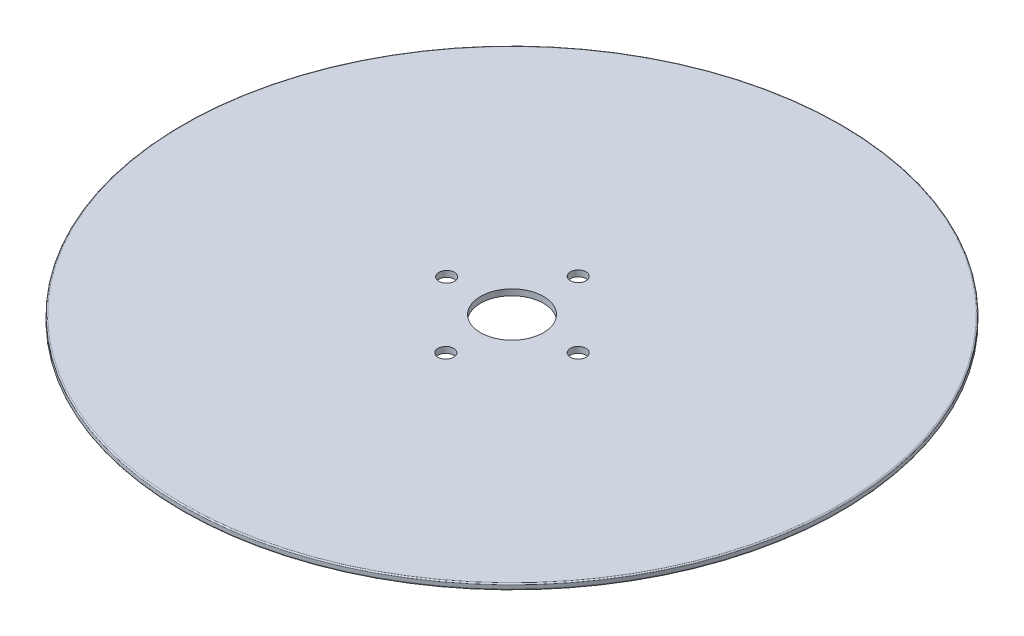
SolidWorks part; units mm, degrees
material "1060 Alloy"
ref_plane "Front Plane" through (0, 0, 0) normal (0, 0, 1) x (1, 0, 0)
ref_plane "Top Plane" through (0, 0, 0) normal (0, 1, 0) x (1, 0, 0)
ref_plane "Right Plane" through (0, 0, 0) normal (1, 0, 0) x (0, 0, -1)
sketch "Sketch1" plane through (0, 0, 0) normal (0, 1, 0) x (1, 0, 0)
  circle A0 centre (0, 0) radius 55
  dimension "D1" = 110
extrude "Boss-Extrude1" add sketch "Sketch1" along normal blind 1
fillet "Fillet2" radius 0.2 2 edges at (0, 1, 55) (0, 0, 55)
sketch "Sketch4" plane through (0, 1, 0) normal (0, 1, 0) x (1, 0, 0)
  circle A0 centre (0, 0) radius 5.25
  dimension "D1" = 10.5
extrude "Cut-Extrude2" cut sketch "Sketch4" against normal through all
sketch "Sketch5" plane through (0, 1, 0) normal (0, 1, 0) x (1, 0, 0)
  line L0 (0, 0) -> (0, 11.05) construction
  line L1 (0, 0) -> (0, -11.05) construction
  line L2 (0, 0) -> (-11.05, 0) construction
  line L3 (0, 0) -> (11.05, 0) construction
  circle A0 centre (-10.9009, 0) radius 1.3
  circle A1 centre (0, 11.05) radius 1.3
  circle A2 centre (11.05, 0) radius 1.3
  circle A3 centre (0, -11.05) radius 1.3
  dimension "D5" = 2.6
  dimension "D6" = 2.6
  dimension "D7" = 2.6
  dimension "D8" = 2.6
  dimension "D1" = 11.05
  dimension "D2" = 11.05
  dimension "D3" = 11.05
  dimension "D4" = 11.05
extrude "Cut-Extrude3" cut sketch "Sketch5" against normal up to surface (1 mm away) up to face at (0, 0, 5.25)
